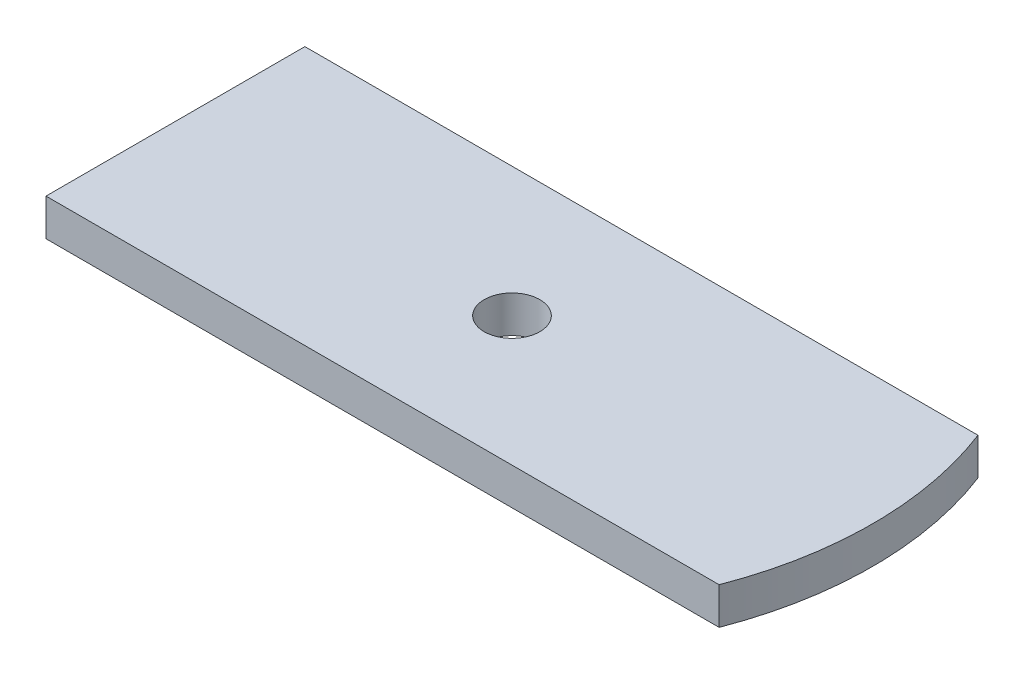
SolidWorks part; units mm, degrees
ref_plane "Front" through (0, 0, 0) normal (0, 0, 1) x (1, 0, 0)
ref_plane "Top" through (0, 0, 0) normal (0, 1, 0) x (1, 0, 0)
ref_plane "Right" through (0, 0, 0) normal (1, 0, 0) x (0, 0, -1)
sketch "Skizze1" plane through (0, 0, 0) normal (0, 1, 0) x (1, 0, 0)
  line L0 (0, 0) -> (0, 62.3766) construction
  line L1 (182.0027, 70) -> (-182.0027, 70)
  line L2 (0, 0) -> (-148.0533, 0) construction
  line L3 (182.0027, -70) -> (-182.0027, -70)
  line L7 (-182.0027, 70) -> (-182.0027, -70)
  arc A0 (15.05, 0) -> (0, -15.05) centre (0, 0) ccw
  arc A1 (-182.0027, 70) -> (-182.0027, -70) centre (0, 0) ccw construction
  circle A3 centre (0, 0) radius 180 construction
  arc A4 (0, -15.05) -> (15.05, 0) centre (0, 0) ccw
  arc A5 (182.0027, 70) -> (182.0027, -70) centre (0, 0) cw
  point P11 (0, 70)
  point P15 (0, -70)
  dimension "D1" = 30.1
  dimension "D3" = 15
  dimension "D2" = 140
extrude "Aufsatz-Linear austragen1" add sketch "Skizze1" along normal blind 20
